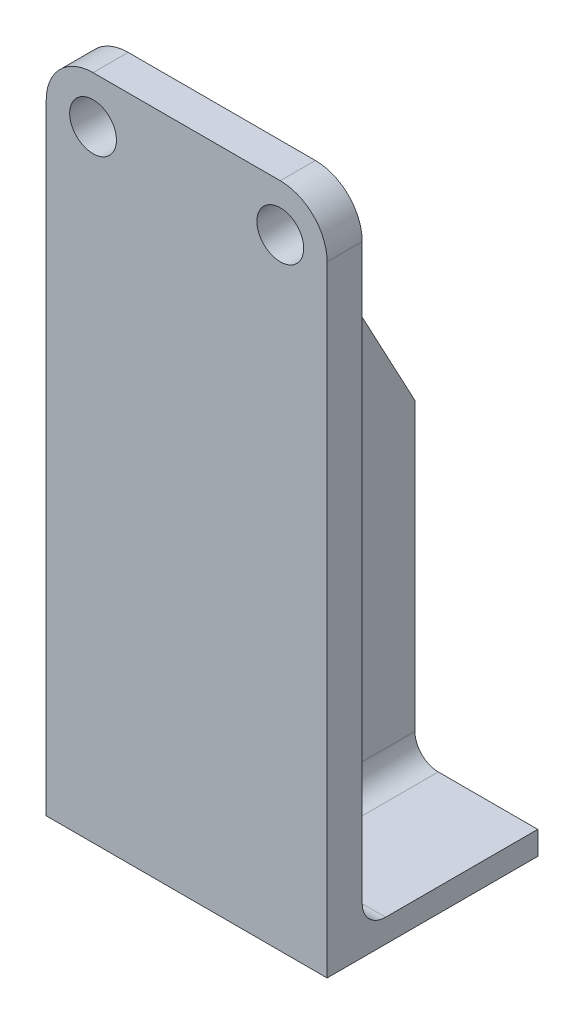
SolidWorks part; units mm, degrees
material "ABS"
ref_plane "Спереди" through (0, 0, 0) normal (0, 0, 1) x (1, 0, 0)
ref_plane "Сверху" through (0, 0, 0) normal (0, 1, 0) x (1, 0, 0)
ref_plane "Справа" through (0, 0, 0) normal (1, 0, 0) x (0, 0, -1)
sketch "Эскиз1" plane through (0, 0, 0) normal (0, 0, 1) x (1, 0, 0)
  line L0 (0, 0) -> (0, 28.6684) construction
  line L1 (0, 0) -> (-31.9827, 0) construction
  line L2 (-8, 30) -> (8, 30)
  line L3 (-12, 26) -> (-12, 0)
  line L4 (12, 26) -> (12, 0)
  line L5 (-12, 0) -> (12, 0)
  circle A0 centre (8, 26) radius 2
  circle A1 centre (-8, 26) radius 2
  arc A2 (-12, 26) -> (-8, 30) centre (-8, 26) cw
  arc A3 (12, 26) -> (8, 30) centre (8, 26) ccw
  circle A4 centre (8, 26) radius 2 construction
  point P17 (0, 30)
  dimension "D3" = 4
  dimension "D4" = 4
extrude "Плоскость" add sketch "Эскиз1" along normal blind 3
sketch "Эскиз2" plane through (0, 0, 0) normal (1, 0, 0) x (0, 0, -1)
  line L0 (0, 0) -> (15, 0)
  line L1 (15, 0) -> (15, 1.5)
  line L2 (15, 1.5) -> (0, 1.5)
  line L3 (0, 0) -> (0, 26) construction
  line L4 (0, 1.5) -> (0, 0)
  dimension "D1" = 1.5
  dimension "D2" = 15
extrude "Основа" add sketch "Эскиз2" along normal up to surface and the other way up to surface up to face at (12, 13, 1.5) other way up to face at (-12, 13, 1.5)
sketch "Эскиз3" plane through (0, 0, 0) normal (1, 0, 0) x (0, 0, -1)
  line L0 (0, 1.5) -> (0, 29.5)
  line L1 (0, 26) -> (0, 30) construction
  line L2 (0, 29.5) -> (15, 1.5)
  line L3 (15, 1.5) -> (0, 1.5)
  dimension "D1" = 28
extrude "Ребро" add sketch "Эскиз3" along normal mid plane 3
sketch "Эскиз6" plane through (0, 1.5, 0) normal (0, 1, 0) x (1, 0, 0)
  line L0 (-12, 0) -> (-1.5, 0) construction
  line L1 (-1.5, 0) -> (-1.5, 15) construction
  line L2 (-1.5, 15) -> (-12, 15) construction
  line L3 (-12, 15) -> (-12, 0) construction
  line L4 (1.5, 15) -> (1.5, 0) construction
  line L5 (1.5, 0) -> (12, 0) construction
  line L6 (12, 0) -> (12, 15) construction
  line L7 (12, 15) -> (1.5, 15) construction
  line L8 (-12, 0) -> (-1.5, 0)
  line L9 (-1.5, 0) -> (-1.5, 15)
  line L10 (-1.5, 15) -> (-12, 15)
  line L11 (-12, 15) -> (-12, 0)
  line L12 (1.5, 15) -> (1.5, 0)
  line L13 (1.5, 0) -> (12, 0)
  line L14 (12, 0) -> (12, 15)
  line L15 (12, 15) -> (1.5, 15)
extrude "Вырез-Вытянуть1" cut sketch "Эскиз6" against normal blind 10
sketch "Эскиз7" plane through (0, 0, 0) normal (0, -1, 0) x (1, 0, 0)
  line L8 (-12, 0) -> (-1.5, 0)
  line L9 (-1.5, 0) -> (-1.5, -15)
  line L10 (-1.5, -15) -> (1.5, -15)
  line L11 (1.5, -15) -> (1.5, 0)
  line L12 (1.5, 0) -> (12, 0)
  line L13 (12, 0) -> (12, 3)
  line L14 (12, 3) -> (-12, 3)
  line L15 (-12, 3) -> (-12, 0)
  line L16 (-12, 0) -> (-1.5, 0)
  line L17 (-1.5, 0) -> (-1.5, -15)
  line L18 (-1.5, -15) -> (1.5, -15)
  line L19 (1.5, -15) -> (1.5, 0)
  line L20 (1.5, 0) -> (12, 0)
  line L21 (12, 0) -> (12, 3)
  line L22 (12, 3) -> (-12, 3)
  line L23 (-12, 3) -> (-12, 0)
  dimension "D1" = 0
extrude "Бобышка-Вытянуть1" add sketch "Эскиз7" along normal blind 25
sketch "Эскиз8" plane through (0, -25, 0) normal (0, -1, 0) x (1, 0, 0)
  line L0 (-12, 3) -> (-12, 0) construction
  line L1 (12, 3) -> (-12, 3) construction
  line L2 (12, 0) -> (12, 3) construction
  line L3 (-1.5, -15) -> (1.5, -15) construction
  line L4 (-12, 3) -> (-12, 0)
  line L5 (12, 3) -> (-12, 3)
  line L6 (12, 0) -> (12, 3)
  line L7 (-1.5, -15) -> (1.5, -15)
  line L9 (-12, 3) -> (12, 3)
  line L10 (-12, 3) -> (-12, -15)
  line L11 (-12, -15) -> (12, -15)
  line L12 (12, 3) -> (12, -15)
  line M1 (-12, 3) -> (-12, 0)
  line M2 (-12, 0) -> (-1.5, 0)
  line M3 (-1.5, 0) -> (-1.5, -15)
  line M4 (-1.5, -15) -> (1.5, -15)
  line M5 (1.5, -15) -> (1.5, 0)
  line M6 (1.5, 0) -> (12, 0)
  line M7 (12, 0) -> (12, 3)
  line M8 (12, 3) -> (-12, 3)
extrude "Бобышка-Вытянуть2" add sketch "Эскиз8" along normal blind 2 contours L10 L11 M3 M2 | L12 L11 M6 M5 | M8 M1 M2 M3 M4 M5 M6 M7
fillet "Скругление1" radius 2 4 edges at (-1.5, -25, -7.5) (1.5, -25, -7.5) (6.75, -25, 0) (-6.75, -25, 0)
